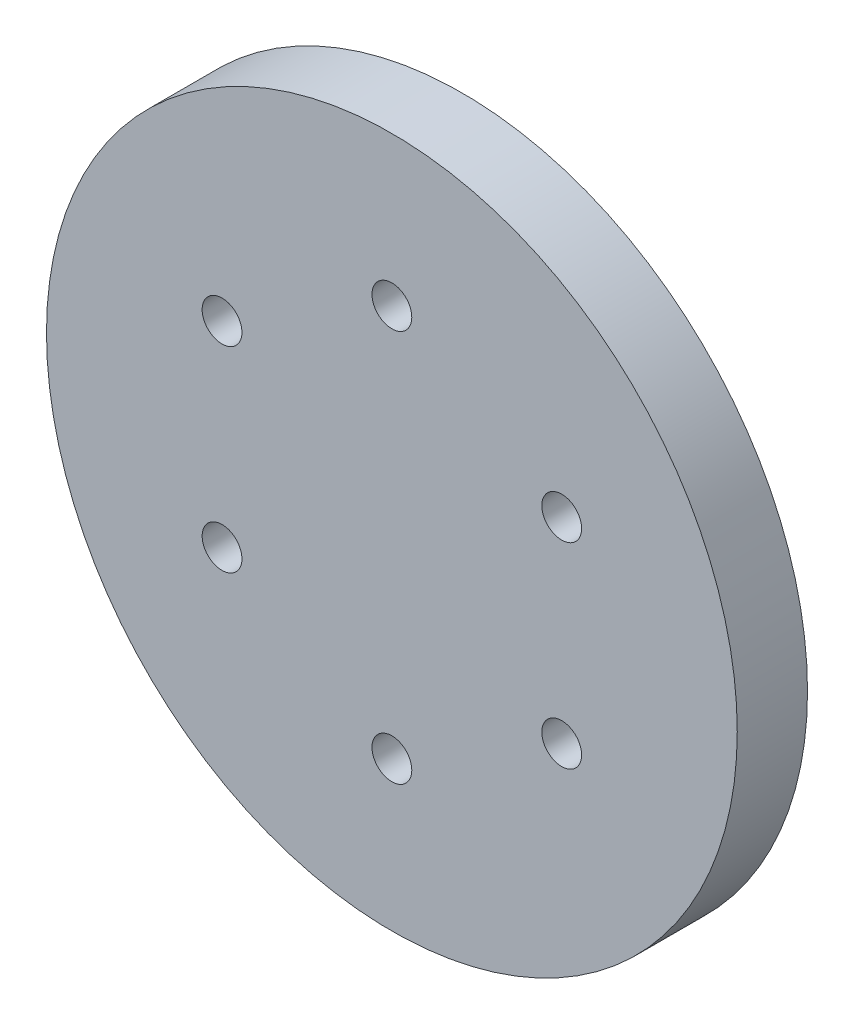
SolidWorks part; units mm, degrees
ref_plane "Front Plane" through (0, 0, 0) normal (0, 0, 1) x (1, 0, 0)
ref_plane "Top Plane" through (0, 0, 0) normal (0, 1, 0) x (1, 0, 0)
ref_plane "Right Plane" through (0, 0, 0) normal (1, 0, 0) x (0, 0, -1)
other "Configuration Table"
sketch "草图1" plane through (0, 0, 0) normal (0, 0, 1) x (1, 0, 0)
  circle A0 centre (0, 0) radius 27.6
  circle A2 centre (-14.5059, -8.375) radius 1.7
  circle A3 centre (-14.5059, 8.375) radius 1.7
  circle A4 centre (0, 16.75) radius 1.7
  circle A5 centre (14.5059, 8.375) radius 1.7
  circle A6 centre (14.5059, -8.375) radius 1.7
  circle A7 centre (0, -16.75) radius 1.7
  point P20 (0, 0)
  dimension "D1" = 55.2
  dimension "D2" = 6
extrude "凸台-拉伸1" add sketch "草图1" along normal blind 3
sketch "草图2" plane through (0, 0, 3) normal (0, 0, 1) x (1, 0, 0)
  circle A0 centre (0, 0) radius 29.5
  circle M5 centre (0, 0) radius 27.6
extrude "凸台-拉伸2" add sketch "草图2" against normal blind 6 contours A0 M5
